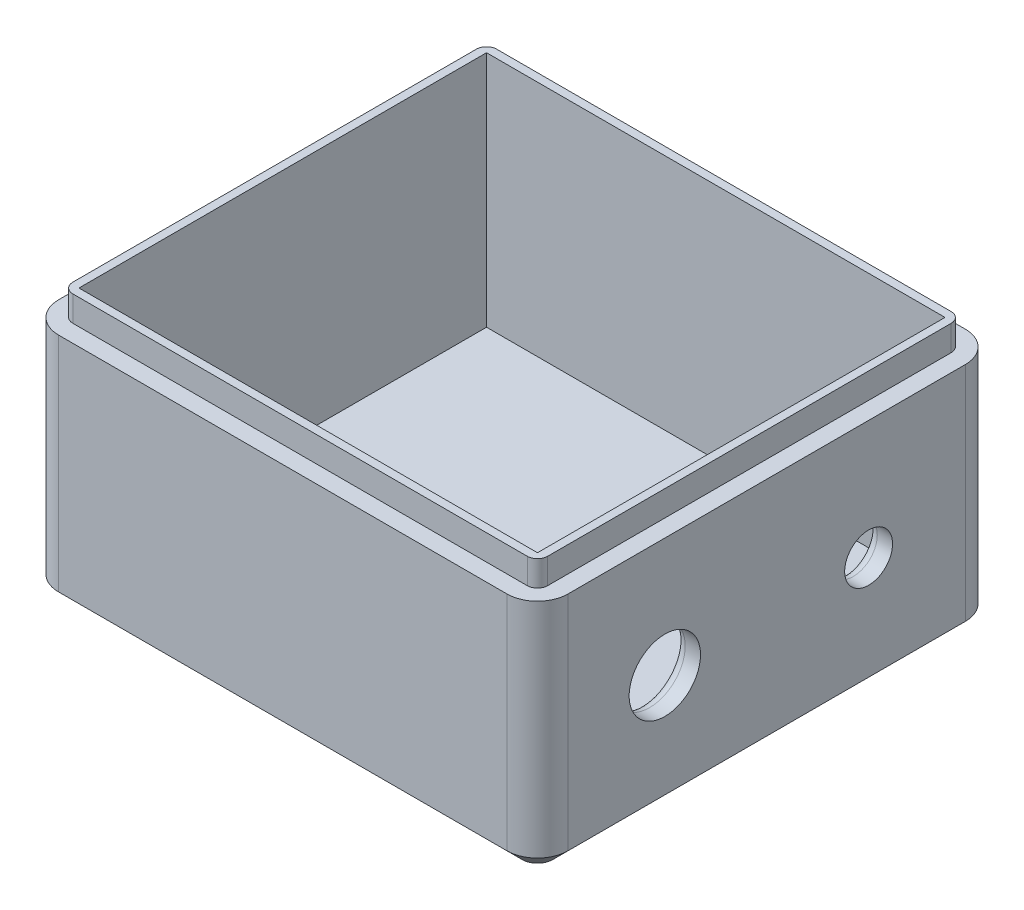
SolidWorks part; units mm, degrees
ref_plane "Front Plane" through (0, 0, 0) normal (0, 0, 1) x (1, 0, 0)
ref_plane "Top Plane" through (0, 0, 0) normal (0, 1, 0) x (1, 0, 0)
ref_plane "Right Plane" through (0, 0, 0) normal (1, 0, 0) x (0, 0, -1)
sketch "Sketch1" plane through (0, 0, 0) normal (0, 0, 1) x (1, 0, 0)
  line L1 (0, 0) -> (50, 0)
  line L2 (0, 0) -> (0, 35)
  line L3 (0, 35) -> (50, 35)
  line L4 (50, 0) -> (50, 35)
  dimension "D1" = 50
  dimension "D2" = 35
extrude "Boss-Extrude1" add sketch "Sketch1" along normal blind 45
sketch "Sketch3" plane through (50, 0, 0) normal (1, 0, 0) x (0, 0, -1)
  line L0 (0, 0) -> (0, 35) construction
  line L1 (-45, 35) -> (0, 35)
  line L2 (-45, 35) -> (-45, 23.3333)
  line L3 (-45, 23.3333) -> (0, 23.3333)
  line L4 (0, 35) -> (0, 23.3333)
  dimension "D1" = 11.6667
extrude "Cut-Extrude2" cut sketch "Sketch3" against normal through all
shell "Shell1" thickness 2.5
sketch "Sketch2" plane through (50, 0, 0) normal (1, 0, 0) x (0, 0, -1)
  line L0 (-45, 11.6667) -> (0, 11.6667) construction
  circle A0 centre (-32.5, 11.6667) radius 3.5
  circle A1 centre (-12.5, 11.6667) radius 2.35
  point P6 (0, 0)
  point P10 (0, 0)
  point P11 (0, 0)
  point P12 (0, 0)
  dimension "D1" = 7
  dimension "D2" = 4.7
  dimension "D3" = 20
  dimension "D4" = 12.5
  dimension "D5" = 11.6667
extrude "Cut-Extrude1" cut sketch "Sketch2" against normal blind 4
sketch "Sketch4" plane through (0, 23.3333, 0) normal (0, 1, 0) x (1, 0, 0)
  line L0 (2.5, -42.5) -> (2.5, -2.5) construction
  line L1 (1.7, -1.7) -> (48.3, -1.7)
  line L2 (1.7, -1.7) -> (1.7, -43.3)
  line L3 (1.7, -43.3) -> (48.3, -43.3)
  line L4 (48.3, -1.7) -> (48.3, -43.3)
  line L5 (47.5, -42.5) -> (47.5, -2.5) construction
  line L6 (2.5, -2.5) -> (47.5, -2.5) construction
  line L7 (2.5, -42.5) -> (47.5, -42.5) construction
  line L9 (2.5, -2.5) -> (47.5, -2.5)
  line L10 (2.5, -2.5) -> (2.5, -42.5)
  line L11 (2.5, -42.5) -> (47.5, -42.5)
  line L12 (47.5, -2.5) -> (47.5, -42.5)
  dimension "D1" = 0.8
  dimension "D2" = 0.8
  dimension "D3" = 0.8
  dimension "D4" = 0.8
extrude "Boss-Extrude2" add sketch "Sketch4" along normal blind 2.5
fillet "Fillet1" radius 3 4 edges at (0, 11.6667, 0) (50, 11.6667, 0) (50, 11.6667, 45) (0, 11.6667, 45)
fillet "Fillet2" radius 1 4 edges at (1.7, 24.5833, 43.3) (1.7, 24.5833, 1.7) (48.3, 24.5833, 1.7) (48.3, 24.5833, 43.3)
chamfer "Chamfer1" distance 1.5 angle 45 8 edges at (0.8787, 0, 0.8787) (0, 0, 22.5) (25, 0, 0) (49.1213, 0, 0.8787) (0.8787, 0, 44.1213) (50, 0, 22.5) (49.1213, 0, 44.1213) (25, 0, 45)
fillet "Fillet3" radius 1 2 edges at (47.5, 11.6667, 36) (47.5, 11.6667, 14.85)
